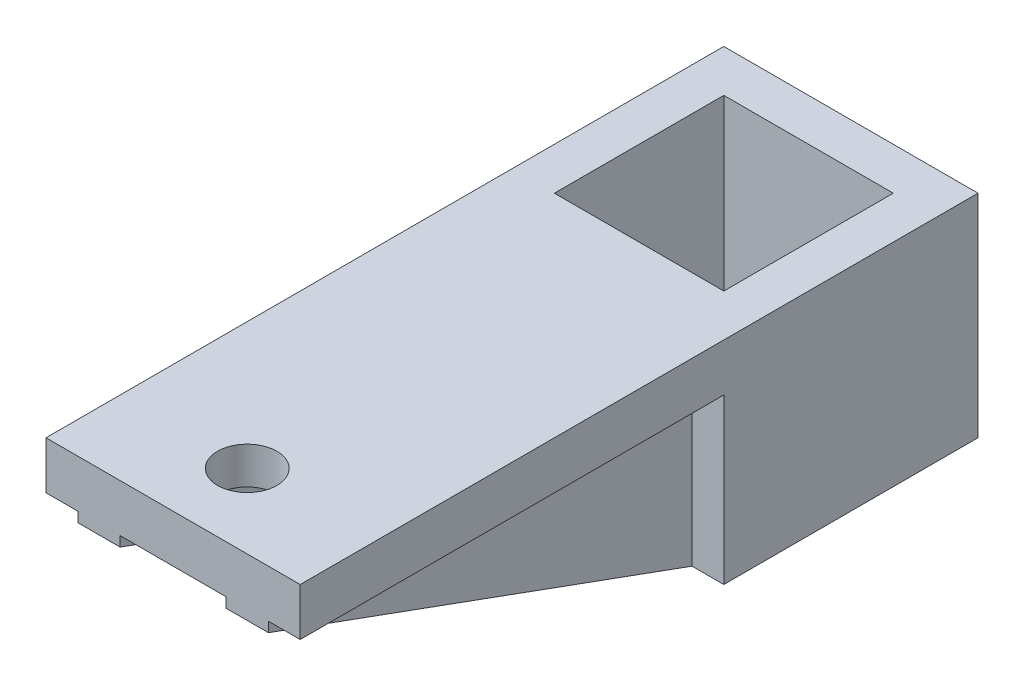
SolidWorks part; units mm, degrees
ref_plane "前视基准面" through (0, 0, 0) normal (0, 0, 1) x (1, 0, 0)
ref_plane "上视基准面" through (0, 0, 0) normal (0, 1, 0) x (1, 0, 0)
ref_plane "右视基准面" through (0, 0, 0) normal (1, 0, 0) x (0, 0, -1)
other "Configuration Table"
sketch "草图1" plane through (0, 0, 0) normal (0, 1, 0) x (1, 0, 0)
  line L0 (-4, -4) -> (-4, 20)
  line L1 (0, 0) -> (16, 0)
  line L2 (0, 0) -> (0, 16)
  line L3 (0, 16) -> (16, 16)
  line L4 (16, 0) -> (16, 16)
  line L5 (-4, 20) -> (20, 20)
  line L6 (20, -4) -> (20, 20)
  line L7 (-4, -4) -> (20, -4)
  dimension "D1" = 16
  dimension "D2" = 16
  dimension "D3" = 4
extrude "凸台-拉伸1" add sketch "草图1" along normal blind 20
sketch "草图2" plane through (0, 0, 4) normal (0, 0, 1) x (1, 0, 0)
  line L0 (20, 20) -> (20, 0) construction
  line L1 (-4, 20) -> (20, 20)
  line L2 (-4, 20) -> (-4, 15.5)
  line L3 (-4, 15.5) -> (20, 15.5)
  line L4 (20, 20) -> (20, 15.5)
  line L5 (-4, 0) -> (20, 0) construction
  dimension "D1" = 15.5
extrude "凸台-拉伸2" add sketch "草图2" along normal blind 40
sketch "草图3" plane through (0, 15.5, 0) normal (0, -1, 0) x (-1, 0, 0)
  line L0 (-20, -44) -> (4, -44) construction
  line L1 (4, -4) -> (-20, -4) construction
  circle A0 centre (-8, -37) radius 2.8
  point P4 (-8, -44)
  dimension "D1" = 0
  dimension "D2" = 33
  dimension "D3" = 5.6
extrude "切除-拉伸1" cut sketch "草图3" against normal blind 40 and the other way blind 40
sketch "草图6" plane through (0, 15.5, 0) normal (0, -1, 0) x (-1, 0, 0)
  line L0 (4, -44) -> (-20, -44) construction
  line L1 (1, -44) -> (-3, -44)
  line L2 (1, -44) -> (1, -4)
  line L3 (1, -4) -> (-3, -4)
  line L4 (-3, -44) -> (-3, -4)
  line L5 (4, -4) -> (-20, -4) construction
  line L6 (-20, -44) -> (-20, -4) construction
  line L7 (-13, -44) -> (-17, -44)
  line L8 (-13, -44) -> (-13, -4)
  line L9 (-13, -4) -> (-17, -4)
  line L10 (-17, -44) -> (-17, -4)
  line L11 (4, -44) -> (4, -4) construction
  dimension "D1" = 4
  dimension "D2" = 4
  dimension "D3" = 3
  dimension "D4" = 3
extrude "凸台-拉伸3" add sketch "草图6" along normal up to surface (15.5 mm away) up to face at (8, 0, -8)
chamfer "倒角1" distance 40 angle 20 2 edges at (1, 0, 44) (15, 0, 44)
sketch "草图7" plane through (0, 15.5, 0) normal (0, -1, 0) x (-1, 0, 0)
  circle A0 centre (-8, -37) radius 5
extrude "切除-拉伸2" cut sketch "草图7" against normal blind 1
